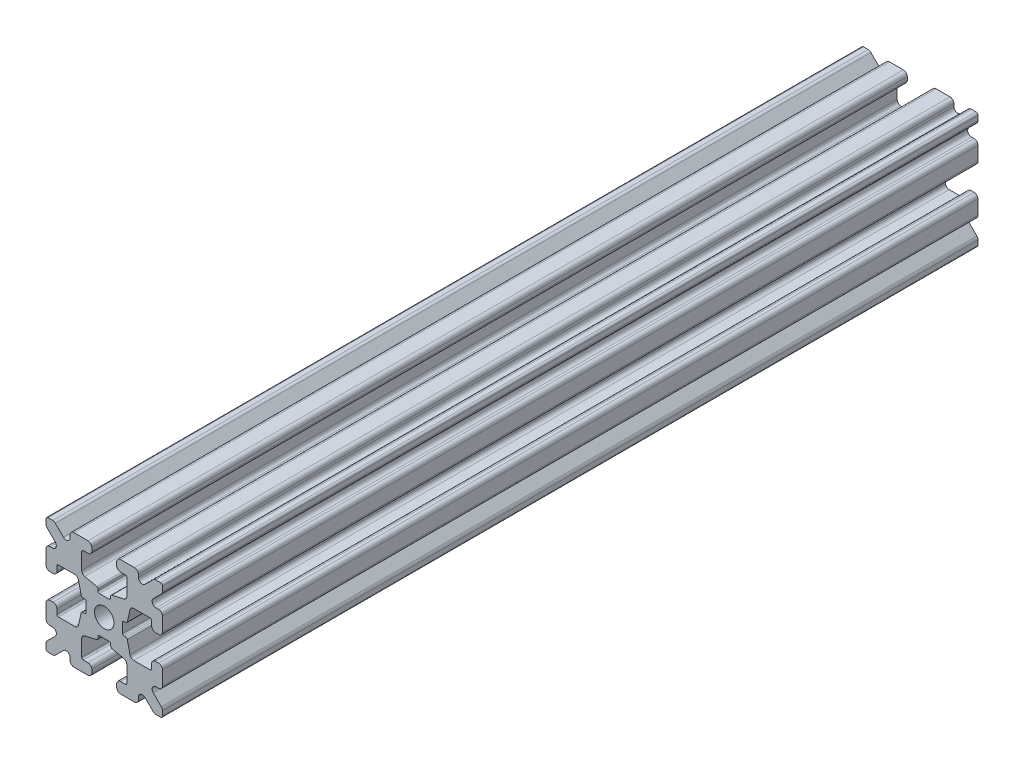
SolidWorks part; units mm, degrees
ref_plane "Front Plane" through (0, 0, 0) normal (0, 0, 1) x (1, 0, 0)
ref_plane "Top Plane" through (0, 0, 0) normal (0, 1, 0) x (1, 0, 0)
ref_plane "Right Plane" through (0, 0, 0) normal (1, 0, 0) x (0, 0, -1)
sketch "Sketch1" plane through (0, 0, 0) normal (0, 0, 1) x (1, 0, 0)
  line L1 (-7.5, -7.5) -> (7.5, -7.5)
  line L2 (-7.5, -7.5) -> (-7.5, 7.5)
  line L3 (-7.5, 7.5) -> (7.5, 7.5)
  line L4 (7.5, -7.5) -> (7.5, 7.5)
  line L5 (-7.5, -7.5) -> (7.5, 7.5) construction
  line L6 (-7.5, 7.5) -> (7.5, -7.5) construction
  circle A0 centre (0, 0) radius 1.25
  point P0 (0, 0)
  dimension "D2" = 2.5
  dimension "D1" = 15
extrude "Boss-Extrude1" add sketch "Sketch1" along normal mid plane 105
fillet "Fillet1" radius 0.25 4 edges at (7.5, -7.5, 0) (-7.5, -7.5, 0) (7.5, 7.5, 0) (-7.5, 7.5, 0)
sketch "Sketch2" plane through (0, 0, 52.5) normal (0, 0, 1) x (1, 0, 0)
  line L0 (-7.5, 7.25) -> (-7.5, -7.25) construction
  line L1 (-7.5, 1.6) -> (-6.1, 1.6)
  line L2 (-7.5, 1.6) -> (-7.5, -1.6)
  line L3 (-7.5, -1.6) -> (-6.1, -1.6)
  line L4 (-6.1, 1.6) -> (-6.1, 2.9)
  line L5 (0, 0) -> (-12.1036, 0) construction
  line L6 (-6.1, -2.9) -> (-3.4, -2.9)
  line L7 (0, 0) -> (-7.25, 7.25) construction
  line L8 (-6.1, 2.9) -> (-3.4, 2.9)
  line L9 (-3.4, -2.9) -> (-3.4, 2.9)
  line L10 (55, 0) -> (-55, 0) construction
  line L11 (-6.1, -2.9) -> (-6.1, -1.6)
  line L12 (2.9, 6.1) -> (1.6, 6.1)
  line L13 (2.9, 3.4) -> (-2.9, 3.4)
  line L14 (-2.9, 6.1) -> (-2.9, 3.4)
  line L15 (2.9, 6.1) -> (2.9, 3.4)
  line L16 (-1.6, 6.1) -> (-2.9, 6.1)
  line L17 (1.6, 7.5) -> (1.6, 6.1)
  line L18 (-1.6, 7.5) -> (1.6, 7.5)
  line L19 (-1.6, 7.5) -> (-1.6, 6.1)
  line L20 (-1.6, -7.5) -> (-1.6, -6.1)
  line L21 (-1.6, -7.5) -> (1.6, -7.5)
  line L22 (1.6, -7.5) -> (1.6, -6.1)
  line L23 (-1.6, -6.1) -> (-2.9, -6.1)
  line L24 (2.9, -6.1) -> (2.9, -3.4)
  line L25 (-2.9, -6.1) -> (-2.9, -3.4)
  line L26 (2.9, -3.4) -> (-2.9, -3.4)
  line L27 (2.9, -6.1) -> (1.6, -6.1)
  line L28 (6.1, -2.9) -> (6.1, -1.6)
  line L29 (3.4, -2.9) -> (3.4, 2.9)
  line L30 (6.1, 2.9) -> (3.4, 2.9)
  line L31 (6.1, -2.9) -> (3.4, -2.9)
  line L32 (6.1, 1.6) -> (6.1, 2.9)
  line L33 (7.5, -1.6) -> (6.1, -1.6)
  line L34 (7.5, 1.6) -> (7.5, -1.6)
  line L35 (7.5, 1.6) -> (6.1, 1.6)
  dimension "D1" = 3.2
  dimension "D2" = 5.8
  dimension "D3" = 1.4
  dimension "D4" = 2.7
extrude "Cut-Extrude1" cut sketch "Sketch2" against normal through all
sketch "Sketch4" plane through (0, 0, 52.5) normal (0, 0, 1) x (1, 0, 0)
  line L0 (-3.4, 2.9) -> (-2.75, 0)
  line L1 (55, 0) -> (-55, 0) construction
  line L2 (-2.75, 0) -> (-3.4, -2.9)
  line L3 (-3.4, -2.9) -> (-3.4, 2.9) construction
  line L4 (-3.4, 2.9) -> (-3.4, -2.9)
  line L5 (-2.9, 3.4) -> (0, 2.75)
  line L6 (0, 2.75) -> (2.9, 3.4)
  line L7 (2.9, 3.4) -> (-2.9, 3.4)
  line L8 (3.4, 2.9) -> (2.75, 0)
  line L9 (2.75, 0) -> (3.4, -2.9)
  line L10 (3.4, -2.9) -> (3.4, 2.9)
  line L11 (-2.9, -3.4) -> (0, -2.75)
  line L12 (0, -2.75) -> (2.9, -3.4)
  line L13 (2.9, -3.4) -> (-2.9, -3.4)
  circle A2 centre (0, 0) radius 2.75
  circle A3 centre (0, 0) radius 2.75 construction
  dimension "D1" = 1.5
extrude "Cut-Extrude3" cut sketch "Sketch4" against normal through all
fillet "Fillet3" radius 0.5 16 edges at (-6.1, -1.6, 0) (-7.5, -1.6, 0) (-6.1, 1.6, 0) (-7.5, 1.6, 0) (-1.6, -7.5, 0) (-1.6, -6.1, 0) (1.6, -7.5, 0) (1.6, -6.1, 0) (6.1, -1.6, 0) (7.5, -1.6, 0) (7.5, 1.6, 0) (6.1, 1.6, 0) (1.6, 7.5, 0) (1.6, 6.1, 0) (-1.6, 7.5, 0) (-1.6, 6.1, 0)
fillet "Fillet4" radius 0.5 8 edges at (-3.4, 2.9, 0) (-3.4, -2.9, 0) (2.9, -3.4, 0) (-2.9, -3.4, 0) (3.4, -2.9, 0) (3.4, 2.9, 0) (-2.9, 3.4, 0) (2.9, 3.4, 0)
fillet "Fillet5" radius 3 4 edges at (0, -2.75, 0) (2.75, 0, 0) (-2.75, 0, 0) (0, 2.75, 0)
fillet "Fillet6" radius 0.2 8 edges at (-2.9, -6.1, 0) (2.9, -6.1, 0) (6.1, -2.9, 0) (6.1, 2.9, 0) (2.9, 6.1, 0) (-2.9, 6.1, 0) (-6.1, -2.9, 0) (-6.1, 2.9, 0)
sketch "Sketch5" plane through (0, 0, 52.5) normal (0, 0, 1) x (1, 0, 0)
  line L0 (0, 0) -> (-7.25, 7.25) construction
  line L1 (-7.5, 6.4393) -> (-5.4607, 4.4)
  line L2 (-6.4393, 7.5) -> (-4.4, 5.4607)
  line L3 (-7.5, 4.4) -> (-5.4607, 4.4)
  line L4 (-3.8003, 2.9) -> (-5.9, 2.9) construction
  line L5 (0, 0) -> (-12.1819, 0) construction
  line L6 (-4.4, 7.5) -> (-4.4, 5.4607)
  line L7 (-2.9, 5.9) -> (-2.9, 3.8003) construction
  line L8 (-7.5, 6.4393) -> (-7.5, 4.4)
  line L9 (-7.5, 7.25) -> (-7.5, 2.1) construction
  line L10 (2.1, -7.5) -> (7.25, -7.5) construction
  line L11 (7.5, -7.25) -> (7.5, -2.1) construction
  line L12 (7.25, 7.5) -> (2.1, 7.5) construction
  line L13 (-2.1, 7.5) -> (-7.25, 7.5) construction
  line L14 (-4.4, 7.5) -> (-6.4393, 7.5)
  line L16 (55, 0) -> (-55, 0) construction
  line L17 (0, 0) -> (0, 10.993) construction
  line L18 (0, -54.6431) -> (0, 54.6431) construction
  line L20 (4.4, 7.5) -> (6.4393, 7.5)
  line L22 (7.5, 6.4393) -> (7.5, 4.4)
  line L23 (4.4, 7.5) -> (4.4, 5.4607)
  line L24 (7.5, 4.4) -> (5.4607, 4.4)
  line L25 (6.4393, 7.5) -> (4.4, 5.4607)
  line L26 (7.5, 6.4393) -> (5.4607, 4.4)
  line L27 (7.5, -6.4393) -> (5.4607, -4.4)
  line L28 (6.4393, -7.5) -> (4.4, -5.4607)
  line L29 (7.5, -4.4) -> (5.4607, -4.4)
  line L30 (4.4, -7.5) -> (4.4, -5.4607)
  line L31 (7.5, -6.4393) -> (7.5, -4.4)
  line L33 (4.4, -7.5) -> (6.4393, -7.5)
  line L36 (-4.4, -7.5) -> (-6.4393, -7.5)
  line L38 (-7.5, -6.4393) -> (-7.5, -4.4)
  line L39 (-4.4, -7.5) -> (-4.4, -5.4607)
  line L40 (-7.5, -4.4) -> (-5.4607, -4.4)
  line L41 (-6.4393, -7.5) -> (-4.4, -5.4607)
  line L42 (-7.5, -6.4393) -> (-5.4607, -4.4)
  dimension "D1" = 1.5
  dimension "D2" = 1.5
  dimension "D3" = 1.5
extrude "Cut-Extrude4" cut sketch "Sketch5" against normal through all
fillet "Fillet8" radius 0.5 24 edges at (-5.4607, 4.4, 0) (-7.5, 4.4, 0) (-5.4607, -4.4, 0) (-7.5, -4.4, 0) (-4.4, -7.5, 0) (-4.4, -5.4607, 0) (4.4, -7.5, 0) (4.4, -5.4607, 0) (5.4607, -4.4, 0) (7.5, -4.4, 0) (7.5, 4.4, 0) (5.4607, 4.4, 0) (4.4, 5.4607, 0) (4.4, 7.5, 0) (-4.4, 5.4607, 0) (-4.4, 7.5, 0) (-6.4393, 7.5, 0) (-7.5, 6.4393, 0) (6.4393, 7.5, 0) (7.5, 6.4393, 0) (6.4393, -7.5, 0) (7.5, -6.4393, 0) (-6.4393, -7.5, 0) (-7.5, -6.4393, 0)
sketch "Sketch6" plane through (0, 0, 52.5) normal (0, 0, 1) x (1, 0, 0)
  line L0 (0, 0) -> (0, 11.013) construction
  line L1 (0.6561, 2.8971) -> (2.1235, 2.8971) construction
  line L2 (0, -54.6431) -> (0, 54.6431) construction
  line L3 (0, 0) -> (7.25, 7.25) construction
  line L4 (7.5, 0.8255) -> (7.5, -0.8255)
  line L5 (2.3471, 0.8255) -> (7.5, 0.8255)
  line L6 (0, 0) -> (12.4016, 0) construction
  line L7 (0.8255, -7.5) -> (-0.8255, -7.5)
  line L8 (2.3471, -0.8255) -> (2.3471, 0.8255)
  line L9 (0.8255, -2.3471) -> (0.8255, -7.5)
  line L10 (7.5, -0.8255) -> (2.3471, -0.8255)
  line L11 (-7.5, -0.8255) -> (-2.3471, -0.8255)
  line L12 (-2.3471, -0.8255) -> (-2.3471, 0.8255)
  line L13 (-0.8255, -2.3471) -> (0.8255, -2.3471)
  line L14 (-0.8255, 7.5) -> (-0.8255, 2.3471)
  line L15 (-0.8255, 2.3471) -> (0.8255, 2.3471)
  line L16 (-0.8255, -7.5) -> (-0.8255, -2.3471)
  line L17 (0.8255, 2.3471) -> (0.8255, 7.5)
  line L18 (0.8255, 7.5) -> (-0.8255, 7.5)
  line L19 (3.9, 7.5) -> (2.1, 7.5) construction
  line L20 (-2.3471, 0.8255) -> (-7.5, 0.8255)
  line L21 (-7.5, 0.8255) -> (-7.5, -0.8255)
  point P5 (0, -2.5973)
  point P7 (0, 2.5973)
  dimension "D3" = 0.55
  dimension "D1" = 1.651
extrude "Cut-Extrude5" cut sketch "Sketch6" against normal through all
fillet "Fillet10" radius 0.2 16 edges at (-2.935, 0.8255, 0) (-2.935, -0.8255, 0) (2.935, -0.8255, 0) (2.935, 0.8255, 0) (0.8255, 2.935, 0) (-0.8255, 2.935, 0) (-2.3471, 0.8255, 0) (-2.3471, -0.8255, 0) (0.8255, 2.3471, 0) (-0.8255, 2.3471, 0) (2.3471, 0.8255, 0) (2.3471, -0.8255, 0) (0.8255, -2.935, 0) (0.8255, -2.3471, 0) (-0.8255, -2.3471, 0) (-0.8255, -2.935, 0)
